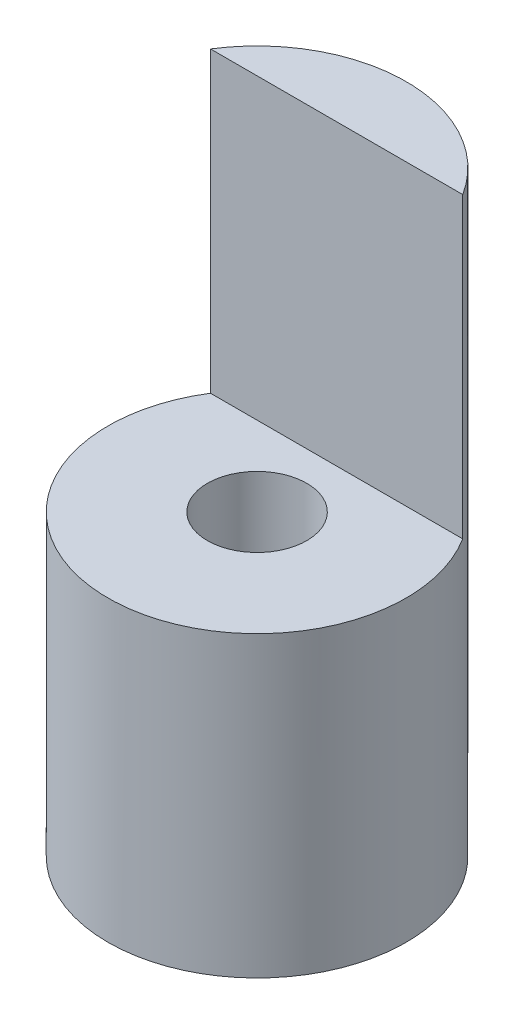
SolidWorks part; units mm, degrees
ref_plane "Alzado" through (0, 0, 0) normal (0, 0, 1) x (1, 0, 0)
ref_plane "Planta" through (0, 0, 0) normal (0, 1, 0) x (1, 0, 0)
ref_plane "Vista lateral" through (0, 0, 0) normal (1, 0, 0) x (0, 0, -1)
sketch "Croquis1" plane through (0, 0, 0) normal (0, 1, 0) x (1, 0, 0)
  circle A0 centre (0, 0) radius 7.5
  dimension "D1" = 15
extrude "Saliente-Extruir1" add sketch "Croquis1" along normal mid plane 30
sketch "Croquis3" plane through (0, 15, 0) normal (0, 1, 0) x (1, 0, 0)
  circle A1 centre (0, 0) radius 2.5
  dimension "D1" = 5
extrude "Cortar-Extruir2" cut sketch "Croquis3" against normal through all
sketch "Croquis2" plane through (0, 15, 0) normal (0, 1, 0) x (1, 0, 0)
  line L1 (-6.3443, 4) -> (6.3443, 4)
  arc A0 (-6.3443, 4) -> (6.3443, 4) centre (0, 0) ccw
  point P5 (-10, 7)
  point P6 (10, 7)
  dimension "D2" = 7.5
  dimension "D1" = 4
extrude "Cortar-Extruir1" cut sketch "Croquis2" against normal blind 15
ref_plane "Plano1" through (0, 0, 7.5) normal (0, 0, 1) x (1, 0, 0)
sketch "Croquis7" plane through (0, -5, 10) normal (0, 0, 1) x (1, 0, 0)
  line L0 (10, 0) -> (-10, 0) construction
  line L1 (0, 5) -> (0, -5) construction
  circle A0 centre (0, -5) radius 1.75
  dimension "D2" = 3.5
  dimension "D1" = 5
extrude "Cortar-Extruir3" cut sketch "Croquis7" against normal up to next
cosmetic thread "Rosca cosmética2" parameters "D2"=4
ref_plane "Plano2" through (0, 0, 0) normal (-1, 0, 0) x (0, 0, 1)
